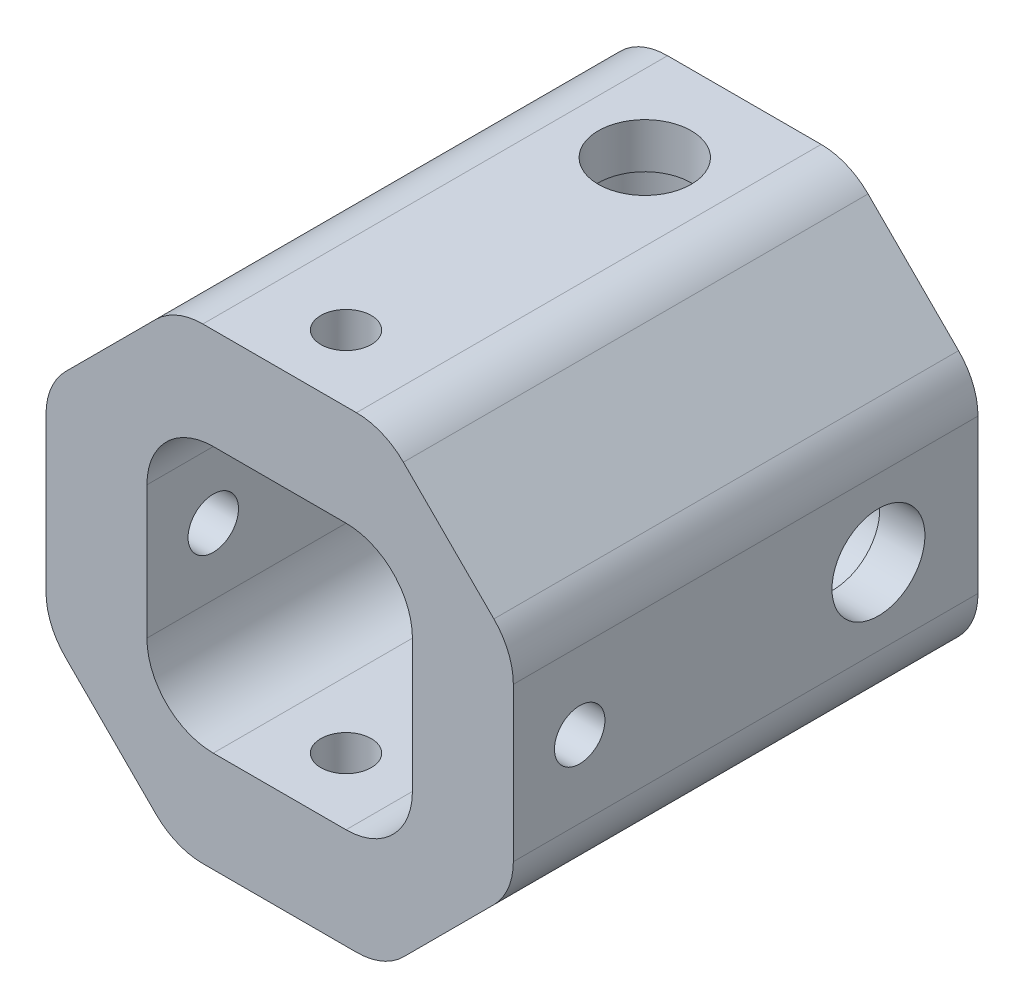
SolidWorks part; units mm, degrees
ref_plane "正面" through (0, 0, 0) normal (0, 0, 1) x (1, 0, 0)
ref_plane "平面" through (0, 0, 0) normal (0, 1, 0) x (1, 0, 0)
ref_plane "右側面" through (0, 0, 0) normal (1, 0, 0) x (0, 0, -1)
sketch "ｽｹｯﾁ1" plane through (0, 0, 0) normal (0, 0, 1) x (1, 0, 0)
  line L0 (7.4558, -18) -> (18, -7.4558)
  line L1 (-18, 7.4558) -> (-18, -7.4558)
  line L2 (-18, -7.4558) -> (-7.4558, -18)
  line L3 (-7.4558, -18) -> (7.4558, -18)
  line L4 (18, -7.4558) -> (18, 7.4558)
  line L5 (18, 7.4558) -> (7.4558, 18)
  line L6 (7.4558, 18) -> (-7.4558, 18)
  line L7 (-7.4558, 18) -> (-18, 7.4558)
  circle A0 centre (0, 0) radius 18 construction
  point P1 (0, -18)
  point P12 (-18, 0)
  dimension "D1" = 18
extrude "ﾎﾞｽ - 押し出し1" add sketch "ｽｹｯﾁ1" along normal mid plane 15
sketch "ｽｹｯﾁ2" plane through (0, 0, 7.5) normal (0, 0, 1) x (1, 0, 0)
  line L0 (7.4558, 18) -> (-7.4558, 18) construction
  line L1 (10, -10) -> (-10, -10)
  line L2 (10, -10) -> (10, 10)
  line L3 (10, 10) -> (-10, 10)
  line L4 (-10, -10) -> (-10, 10)
  line L5 (10, -10) -> (-10, 10) construction
  line L6 (10, 10) -> (-10, -10) construction
  line L7 (18, -7.4558) -> (18, 7.4558) construction
  point P0 (0, 0)
  dimension "D1" = 8
  dimension "D2" = 8
extrude "ｶｯﾄ - 押し出し1" cut sketch "ｽｹｯﾁ2" against normal through all both and the other way through all
sketch "ｽｹｯﾁ11" plane through (0, 18, 0) normal (0, 1, 0) x (1, 0, 0)
  line L1 (-14.7524, -23.747) -> (14.7524, -23.747)
  line L2 (-14.7524, -23.747) -> (-14.7524, 23.747)
  line L3 (-14.7524, 23.747) -> (14.7524, 23.747)
  line L4 (14.7524, -23.747) -> (14.7524, 23.747)
  line L5 (-14.7524, -23.747) -> (14.7524, 23.747) construction
  line L6 (-14.7524, 23.747) -> (14.7524, -23.747) construction
  point P0 (0, 0)
extrude "ｶｯﾄ - 押し出し7" cut sketch "ｽｹｯﾁ11" against normal blind 0.4
mirror "ﾐﾗｰ1" about plane through (0, 0, 0) normal (0, 1, 0) of "ｶｯﾄ - 押し出し7"
sketch "ｽｹｯﾁ12" plane through (-18, 0, 0) normal (-1, 0, 0) x (0, 0, 1)
  line L1 (-10.119, -12.8597) -> (10.119, -12.8597)
  line L2 (-10.119, -12.8597) -> (-10.119, 12.8597)
  line L3 (-10.119, 12.8597) -> (10.119, 12.8597)
  line L4 (10.119, -12.8597) -> (10.119, 12.8597)
  line L5 (-10.119, -12.8597) -> (10.119, 12.8597) construction
  line L6 (-10.119, 12.8597) -> (10.119, -12.8597) construction
  point P0 (0, 0)
extrude "ｶｯﾄ - 押し出し8" cut sketch "ｽｹｯﾁ12" against normal blind 0.4
mirror "ﾐﾗｰ2" about plane through (0, 0, 0) normal (1, 0, 0) of "ｶｯﾄ - 押し出し8"
fillet "ﾌｨﾚｯﾄ1" radius 5 4 edges at (10, -10, 0) (-10, -10, 0) (10, 10, 0) (-10, 10, 0)
fillet "ﾌｨﾚｯﾄ2" radius 5 8 edges at (17.6, -7.8558, 0) (7.8558, -17.6, 0) (-7.8558, -17.6, 0) (17.6, 7.8558, 0) (-17.6, -7.8558, 0) (-17.6, 7.8558, 0) (7.8558, 17.6, 0) (-7.8558, 17.6, 0)
sketch "ｽｹｯﾁ3" plane through (0, -17.6, 0) normal (0, -1, 0) x (1, 0, 0)
  circle A0 centre (0, 0) radius 4.2
  dimension "D1" = 8.4
extrude "ｶｯﾄ - 押し出し2" cut sketch "ｽｹｯﾁ3" against normal through all both and the other way through all
sketch "ｽｹｯﾁ4" plane through (17.6, 0, 0) normal (1, 0, 0) x (0, 0, -1)
  circle A0 centre (0, 0) radius 4.2
  dimension "D1" = 8.4
extrude "ｶｯﾄ - 押し出し3" cut sketch "ｽｹｯﾁ4" against normal through all both and the other way through all
sketch "ｽｹｯﾁ5" plane through (0, 0, 7.5) normal (0, 0, 1) x (1, 0, 0)
  line L0 (5, 10) -> (-5, 10) construction
  line L1 (10, -5) -> (10, 5) construction
  line L2 (-5, -10) -> (5, -10) construction
  line L3 (-10, 5) -> (-10, -5) construction
  line L4 (5, 10) -> (-5, 10)
  line L5 (10, -5) -> (10, 5)
  line L6 (-5, -10) -> (5, -10)
  line L7 (-10, 5) -> (-10, -5)
  line L8 (9.3203, -16.1355) -> (16.1355, -9.3203)
  line L9 (17.6, -5.7848) -> (17.6, 5.7848)
  line L10 (16.1355, 9.3203) -> (9.3203, 16.1355)
  line L11 (17.6, -5.7848) -> (17.6, 5.7848)
  line L12 (-9.3203, 16.1355) -> (-16.1355, 9.3203)
  line L13 (5.7848, 17.6) -> (-5.7848, 17.6)
  line L14 (-16.1355, -9.3203) -> (-9.3203, -16.1355)
  line L15 (5.7848, 17.6) -> (-5.7848, 17.6)
  line L16 (9.3203, -16.1355) -> (16.1355, -9.3203)
  line L18 (16.1355, 9.3203) -> (9.3203, 16.1355)
  line L20 (-9.3203, 16.1355) -> (-16.1355, 9.3203)
  line L22 (-16.1355, -9.3203) -> (-9.3203, -16.1355)
  line L32 (-17.6, 5.7848) -> (-17.6, -5.7848)
  line L33 (-17.6, 5.7848) -> (-17.6, -5.7848)
  line L34 (-5.7848, -17.6) -> (5.7848, -17.6)
  line L35 (-5.7848, -17.6) -> (5.7848, -17.6)
  arc A0 (-5, 10) -> (-10, 5) centre (-5, 5) ccw construction
  arc A1 (-5, 10) -> (-10, 5) centre (-5, 5) ccw
  arc A2 (10, 5) -> (5, 10) centre (5, 5) ccw construction
  arc A3 (5, -10) -> (10, -5) centre (5, -5) ccw construction
  arc A4 (-10, -5) -> (-5, -10) centre (-5, -5) ccw construction
  arc A5 (10, 5) -> (5, 10) centre (5, 5) ccw
  arc A6 (5, -10) -> (10, -5) centre (5, -5) ccw
  arc A7 (-10, -5) -> (-5, -10) centre (-5, -5) ccw
  arc A24 (16.1355, -9.3203) -> (17.6, -5.7848) centre (12.6, -5.7848) ccw
  arc A25 (16.1355, -9.3203) -> (17.6, -5.7848) centre (12.6, -5.7848) ccw
  arc A26 (17.6, 5.7848) -> (16.1355, 9.3203) centre (12.6, 5.7848) ccw
  arc A27 (17.6, 5.7848) -> (16.1355, 9.3203) centre (12.6, 5.7848) ccw
  arc A28 (9.3203, 16.1355) -> (5.7848, 17.6) centre (5.7848, 12.6) ccw
  arc A29 (9.3203, 16.1355) -> (5.7848, 17.6) centre (5.7848, 12.6) ccw
  arc A30 (-5.7848, 17.6) -> (-9.3203, 16.1355) centre (-5.7848, 12.6) ccw
  arc A31 (-5.7848, 17.6) -> (-9.3203, 16.1355) centre (-5.7848, 12.6) ccw
  arc A32 (-16.1355, 9.3203) -> (-17.6, 5.7848) centre (-12.6, 5.7848) ccw
  arc A33 (-16.1355, 9.3203) -> (-17.6, 5.7848) centre (-12.6, 5.7848) ccw
  arc A34 (-17.6, -5.7848) -> (-16.1355, -9.3203) centre (-12.6, -5.7848) ccw
  arc A35 (-17.6, -5.7848) -> (-16.1355, -9.3203) centre (-12.6, -5.7848) ccw
  arc A36 (-9.3203, -16.1355) -> (-5.7848, -17.6) centre (-5.7848, -12.6) ccw
  arc A37 (-9.3203, -16.1355) -> (-5.7848, -17.6) centre (-5.7848, -12.6) ccw
  arc A38 (5.7848, -17.6) -> (9.3203, -16.1355) centre (5.7848, -12.6) ccw
  arc A39 (5.7848, -17.6) -> (9.3203, -16.1355) centre (5.7848, -12.6) ccw
  dimension "D1" = 0
extrude "ﾎﾞｽ - 押し出し2" add sketch "ｽｹｯﾁ5" along normal blind 20
sketch "ｽｹｯﾁ6" plane through (0, -17.6, 0) normal (0, -1, 0) x (1, 0, 0)
  circle A1 centre (0, 0) radius 4.2
  circle A2 centre (0, 0) radius 3.5
  circle A3 centre (0, 0) radius 4.2 construction
  dimension "D1" = 7
extrude "ﾎﾞｽ - 押し出し3" add sketch "ｽｹｯﾁ6" against normal blind 3.4
mirror "ﾐﾗｰ3" about plane through (0, 0, 0) normal (0, 1, 0) of "ﾎﾞｽ - 押し出し3"
sketch "ｽｹｯﾁ13" plane through (-17.6, 0, 0) normal (-1, 0, 0) x (0, 0, 1)
  circle A0 centre (0, 0) radius 4.2 construction
  circle A1 centre (0, 0) radius 4.2
  circle A2 centre (0, 0) radius 3.5
  dimension "D1" = 7
extrude "ﾎﾞｽ - 押し出し4" add sketch "ｽｹｯﾁ13" along direction (-1, 0, 0) on the side against the normal blind 3.4
mirror "ﾐﾗｰ4" about plane through (0, 0, 0) normal (1, 0, 0) of "ﾎﾞｽ - 押し出し4"
sketch "ｽｹｯﾁ14" plane through (-17.6, 0, 0) normal (-1, 0, 0) x (0, 0, 1)
  line L0 (27.5, 5.7848) -> (27.5, -5.7848) construction
  circle A0 centre (22.5, 0) radius 1.9
  dimension "D1" = 3.8
  dimension "D2" = 5
extrude "ｶｯﾄ - 押し出し9" cut sketch "ｽｹｯﾁ14" against normal through all
sketch "ｽｹｯﾁ15" plane through (0, -17.6, 0) normal (0, -1, 0) x (1, 0, 0)
  line L0 (-5.7848, 27.5) -> (5.7848, 27.5) construction
  circle A0 centre (0, 22.5) radius 1.9
  dimension "D1" = 3.8
  dimension "D2" = 5
extrude "ｶｯﾄ - 押し出し10" cut sketch "ｽｹｯﾁ15" against normal through all
